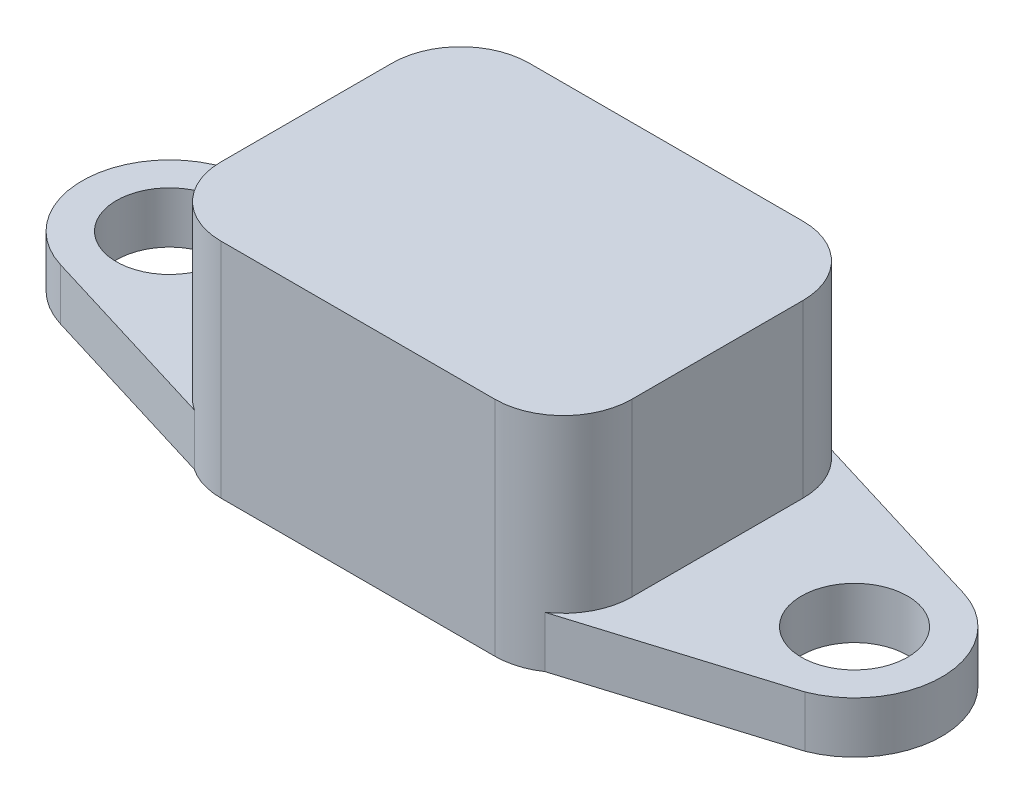
SolidWorks part; units mm, degrees
ref_plane "Front Plane" through (0, 0, 0) normal (0, 0, 1) x (1, 0, 0)
ref_plane "Top Plane" through (0, 0, 0) normal (0, 1, 0) x (1, 0, 0)
ref_plane "Right Plane" through (0, 0, 0) normal (1, 0, 0) x (0, 0, -1)
sketch "Sketch1" plane through (0, 0, 0) normal (0, 1, 0) x (1, 0, 0)
  line L1 (-8, 8) -> (8, 8)
  line L2 (-11, 5) -> (-11, -5)
  line L3 (-8, -8) -> (8, -8)
  line L4 (11, 5) -> (11, -5)
  line L5 (-11, 8) -> (11, -8) construction
  line L6 (-11, -8) -> (11, 8) construction
  line L7 (-8, 9) -> (8, 9)
  line L8 (-12, 5) -> (-12, -5)
  line L9 (-8, -9) -> (8, -9)
  line L10 (12, 5) -> (12, -5)
  line L11 (-12, 9) -> (12, -9) construction
  line L12 (-12, -9) -> (12, 9) construction
  arc A0 (-11, -5) -> (-8, -8) centre (-8, -5) ccw
  arc A1 (8, -8) -> (11, -5) centre (8, -5) ccw
  arc A2 (8, 8) -> (11, 5) centre (8, 5) cw
  arc A3 (-8, 8) -> (-11, 5) centre (-8, 5) ccw
  arc A4 (-12, -5) -> (-8, -9) centre (-8, -5) ccw
  arc A5 (8, -9) -> (12, -5) centre (8, -5) ccw
  arc A6 (8, 9) -> (12, 5) centre (8, 5) cw
  arc A7 (-8, 9) -> (-12, 5) centre (-8, 5) ccw
  point P0 (0, 0)
  point P6 (0, 0)
  dimension "D5" = 3
  dimension "D6" = 4
  dimension "D1" = 22
  dimension "D2" = 16
  dimension "D3" = 1
  dimension "D4" = 1
extrude "Boss-Extrude1" add sketch "Sketch1" along normal blind 12
sketch "Sketch2" plane through (0, 12, 0) normal (0, 1, 0) x (1, 0, 0)
  line L1 (-8, -9) -> (8, -9)
  line L2 (-12, -5) -> (-12, 5)
  line L3 (-8, 9) -> (8, 9)
  line L4 (12, -5) -> (12, 5)
  line L5 (-12, -9) -> (12, 9) construction
  line L6 (-12, 9) -> (12, -9) construction
  arc A0 (-8, -9) -> (-12, -5) centre (-8, -5) cw
  arc A1 (8, -9) -> (12, -5) centre (8, -5) ccw
  arc A2 (8, 9) -> (12, 5) centre (8, 5) cw
  arc A3 (-12, 5) -> (-8, 9) centre (-8, 5) cw
  point P0 (0, 0)
  dimension "D1" = 4
extrude "Boss-Extrude2" add sketch "Sketch2" along normal blind 1
sketch "Sketch3" plane through (0, 0, 0) normal (0, -1, 0) x (1, 0, 0)
  line L0 (-8, 9) -> (-21.4905, 4.8773)
  line L1 (-8, -9) -> (-21.4905, -4.8773)
  line L2 (8, 9) -> (21.8588, 4.7492)
  line L3 (8, -9) -> (21.4905, -4.8773)
  line L4 (-8, 9) -> (-11.9681, 5.5041)
  line L5 (-11.9681, 5.5041) -> (-12, -5)
  line L6 (-12, -5) -> (-10.1213, -7.8284)
  line L7 (-10.1213, -7.8284) -> (-8, -9)
  line L8 (8, 9) -> (10.2792, 7.252)
  line L9 (10.2792, 7.252) -> (12, 5)
  line L10 (12, 5) -> (12, -5)
  line L11 (12, -5) -> (10.7211, -7.3157)
  line L12 (10.7211, -7.3157) -> (8, -9)
  circle A0 centre (-20, 0) radius 3.1
  circle A1 centre (20, 0) radius 3.1
  arc A2 (-21.4905, 4.8773) -> (-21.4905, -4.8773) centre (-20, 0) ccw
  arc A3 (21.4905, -4.8773) -> (21.1237, 4.9747) centre (20, 0) ccw
  arc A4 (8, -9) -> (12, -5) centre (8, -5) ccw construction
  arc A5 (-8, 9) -> (-12, 5) centre (-8, 5) ccw construction
  arc M1 (-8, 9) -> (-12, 5) centre (-8, 5) ccw
  line M2 (-12, 5) -> (-12, -5)
  arc M3 (-12, -5) -> (-8, -9) centre (-8, -5) ccw
  arc M5 (8, -9) -> (12, -5) centre (8, -5) ccw
  line M6 (12, -5) -> (12, 5)
  arc M7 (12, 5) -> (8, 9) centre (8, 5) ccw
  dimension "D1" = 6.2
  dimension "D2" = 6.2
  dimension "D3" = 20
  dimension "D5" = 2
  dimension "D6" = 2
  dimension "D4" = 20
extrude "Boss-Extrude3" add sketch "Sketch3" against normal blind 3 contours L0 A2 L1 A0 M3 M2 M1 | L3 A3 L2 A1 M7 M6 M5
sketch "Sketch4" plane through (0, 12, 0) normal (0, -1, 0) x (1, 0, 0)
  text T0 "<b>Oliver</b>\r\n<b>Proof</b>" font "Century Gothic" height in points 16
extrude "Cut-Extrude1" cut sketch "Sketch4" against normal blind 0.5
